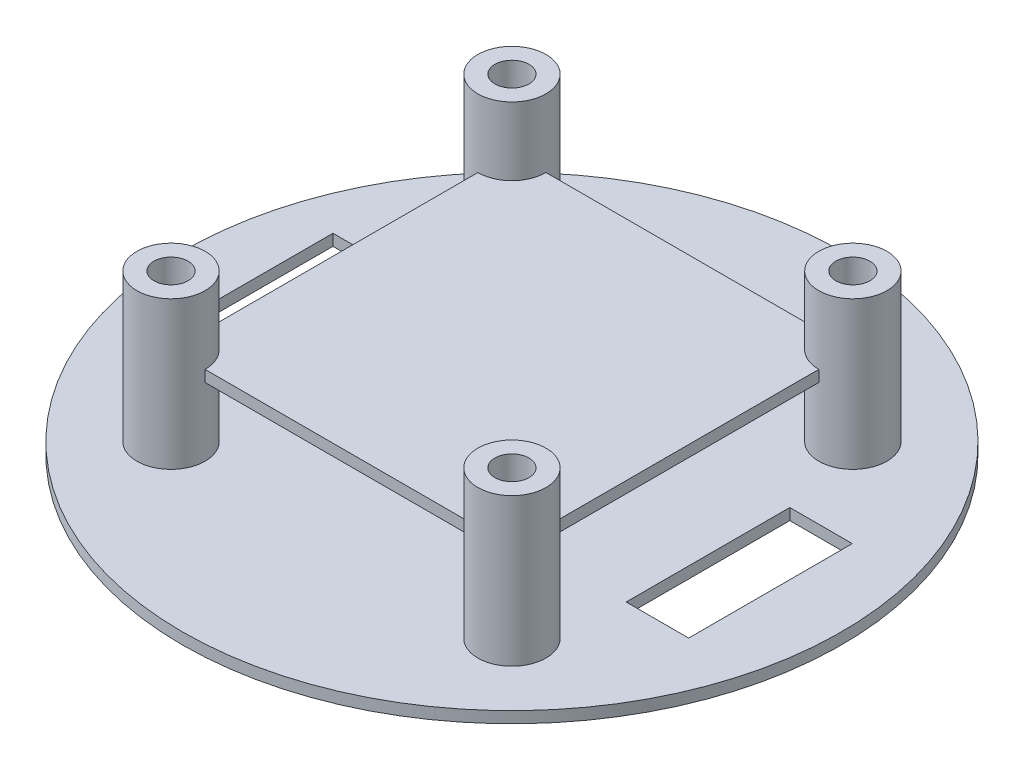
SolidWorks part; units mm, degrees
ref_plane "Alzado" through (0, 0, 0) normal (0, 0, 1) x (1, 0, 0)
ref_plane "Planta" through (0, 0, 0) normal (0, 1, 0) x (1, 0, 0)
ref_plane "Vista lateral" through (0, 0, 0) normal (1, 0, 0) x (0, 0, -1)
sketch "Croquis1" plane through (0, 0, 0) normal (0, 1, 0) x (1, 0, 0)
  circle A0 centre (0, 0) radius 29
  dimension "D1" = 58
extrude "Saliente-Extruir1" add sketch "Croquis1" along normal blind 1
sketch "Croquis2" plane through (0, 1, 0) normal (0, 1, 0) x (1, 0, 0)
  line L1 (-15, -15) -> (15, -15) construction
  line L2 (-15, -15) -> (-15, 15) construction
  line L3 (-15, 15) -> (15, 15) construction
  line L4 (15, -15) -> (15, 15) construction
  line L5 (-15, -15) -> (15, 15) construction
  line L6 (-15, 15) -> (15, -15) construction
  circle A0 centre (-15, 15) radius 3
  circle A1 centre (15, 15) radius 3
  circle A2 centre (-15, -15) radius 3
  circle A3 centre (15, -15) radius 3
  point P0 (0, 0)
  dimension "D1" = 6
  dimension "D3" = 30
  dimension "D4" = 30
extrude "Saliente-Extruir2" add sketch "Croquis2" along normal blind 7
sketch "Croquis3" plane through (0, 8, 0) normal (0, 1, 0) x (1, 0, 0)
  line L0 (-15, -12) -> (-15, 12)
  line L1 (-12, -15) -> (12, -15)
  line L2 (15, -12) -> (15, 12)
  line L3 (-12, 15) -> (12, 15)
  circle A0 centre (-15, -15) radius 3 construction
  circle A1 centre (-15, -15) radius 3 construction
  circle A2 centre (-15, 15) radius 3 construction
  circle A3 centre (15, -15) radius 3 construction
  circle A4 centre (15, -15) radius 3 construction
  circle A5 centre (15, 15) radius 3 construction
  circle A6 centre (-15, 15) radius 3 construction
  arc A7 (-12, 15) -> (-15, 12) centre (-15, 15) cw
  arc A8 (15, 12) -> (12, 15) centre (15, 15) cw
  arc A9 (-12, -15) -> (-15, -12) centre (-15, -15) ccw
  arc A10 (12, -15) -> (15, -12) centre (15, -15) cw
extrude "Saliente-Extruir3" add sketch "Croquis3" against normal blind 1
sketch "Croquis4" plane through (0, 8, 0) normal (0, 1, 0) x (1, 0, 0)
  circle A0 centre (15, 15) radius 3
  circle A1 centre (15, -15) radius 3
  circle A2 centre (-15, 15) radius 3
  circle A3 centre (-15, -15) radius 3
  dimension "D1" = 6
extrude "Saliente-Extruir4" add sketch "Croquis4" along normal blind 6
sketch "Croquis5" plane through (0, 14, 0) normal (0, 1, 0) x (1, 0, 0)
  circle A0 centre (15, 15) radius 1.5
  circle A1 centre (15, -15) radius 1.5
  circle A2 centre (-15, -15) radius 1.5
  circle A3 centre (-15, 15) radius 1.5
  circle A4 centre (-15, 15) radius 3 construction
  circle A5 centre (-15, -15) radius 3 construction
  dimension "D1" = 3
extrude "Cortar-Extruir1" cut sketch "Croquis5" against normal blind 6
sketch "Croquis6" plane through (0, 0, 0) normal (0, -1, 0) x (1, 0, 0)
  line L0 (0, 0) -> (20, 0) construction
  line L1 (17.25, -7.2) -> (22.75, -7.2)
  line L2 (17.25, -7.2) -> (17.25, 7.2)
  line L3 (17.25, 7.2) -> (22.75, 7.2)
  line L4 (22.75, -7.2) -> (22.75, 7.2)
  line L5 (17.25, -7.2) -> (22.75, 7.2) construction
  line L6 (17.25, 7.2) -> (22.75, -7.2) construction
  line L7 (0, 0) -> (-20, 0) construction
  line L9 (-23.75, 8) -> (-16.25, 8)
  line L10 (-23.75, 8) -> (-23.75, -8)
  line L11 (-23.75, -8) -> (-16.25, -8)
  line L12 (-16.25, 8) -> (-16.25, -8)
  line L13 (-23.75, 8) -> (-16.25, -8) construction
  line L14 (-23.75, -8) -> (-16.25, 8) construction
  point P0 (20, 0)
  dimension "D1" = 5.5
  dimension "D2" = 14.4
  dimension "D3" = 20
  dimension "D4" = 20
  dimension "D5" = 7.5
  dimension "D6" = 16
extrude "Cortar-Extruir2" cut sketch "Croquis6" against normal up to next
